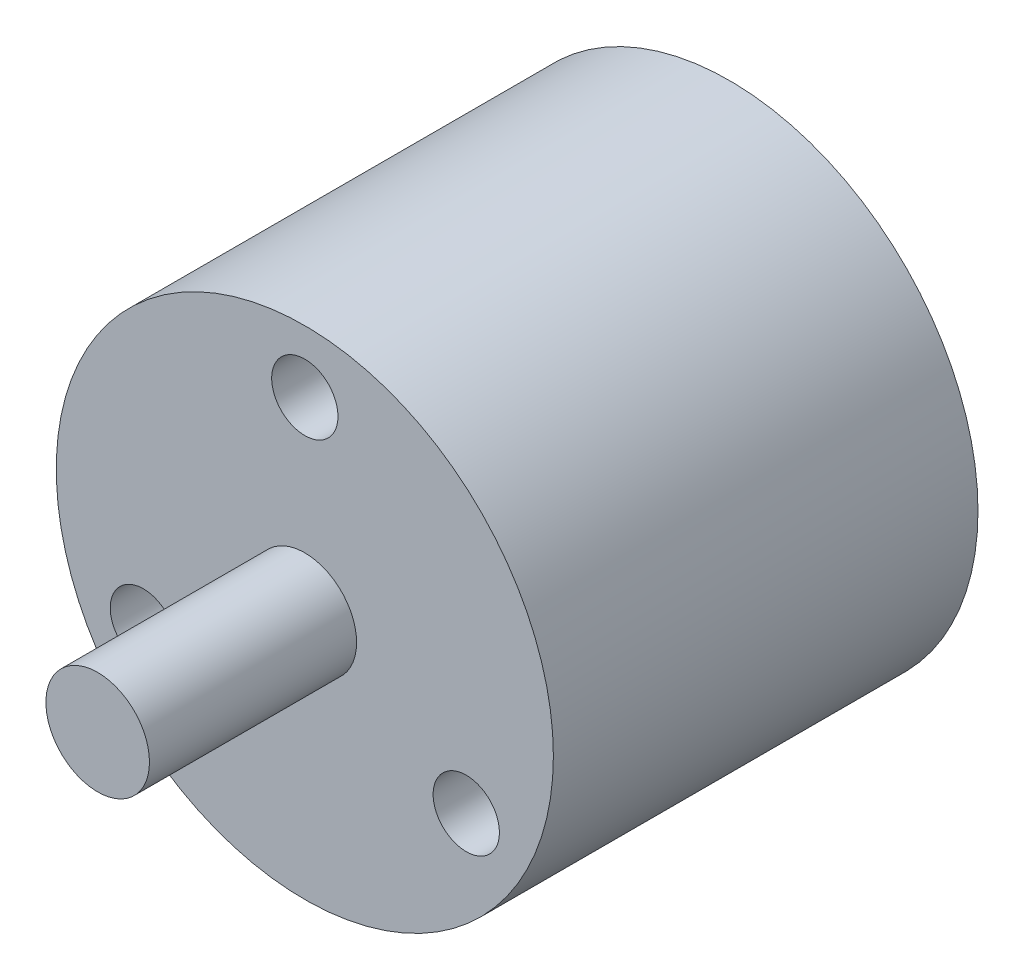
SolidWorks part; units mm, degrees
ref_plane "Plan de face" through (0, 0, 0) normal (0, 0, 1) x (1, 0, 0)
ref_plane "Plan de dessus" through (0, 0, 0) normal (0, 1, 0) x (1, 0, 0)
ref_plane "Plan de droite" through (0, 0, 0) normal (1, 0, 0) x (0, 0, -1)
sketch "Esquisse1" plane through (0, 0, 0) normal (0, 0, 1) x (1, 0, 0)
  circle A0 centre (0, 0) radius 12
  dimension "D1" = 24
extrude "Boss.-Extru.1" add sketch "Esquisse1" along normal blind 20.5
sketch "Esquisse2" plane through (0, 0, 20.5) normal (0, 0, 1) x (1, 0, 0)
  circle A0 centre (0, 0) radius 2.5
  dimension "D1" = 5
extrude "Boss.-Extru.2" add sketch "Esquisse2" along normal blind 2
sketch "Esquisse3" plane through (0, 0, 20.5) normal (0, 0, 1) x (1, 0, 0)
  line L0 (0, 0) -> (0, 9) construction
  line L1 (0, 0) -> (-7.7942, -4.5)
  line L2 (0, 0) -> (7.7942, -4.5)
  circle A0 centre (0, 0) radius 9 construction
  circle A1 centre (0, 9) radius 1.6
  circle A2 centre (-7.7942, -4.5) radius 1.6
  circle A3 centre (7.7942, -4.5) radius 1.6
  dimension "D1" = 120
  dimension "D2" = 120
  dimension "D3" = 9
extrude "Enlèv. mat.-Extru.1" cut sketch "Esquisse3" against normal blind 3
sketch "Esquisse4" plane through (0, 0, 22.5) normal (0, 0, 1) x (1, 0, 0)
  circle A0 centre (0, 0) radius 2.5
extrude "Boss.-Extru.3" add sketch "Esquisse4" along normal blind 8
